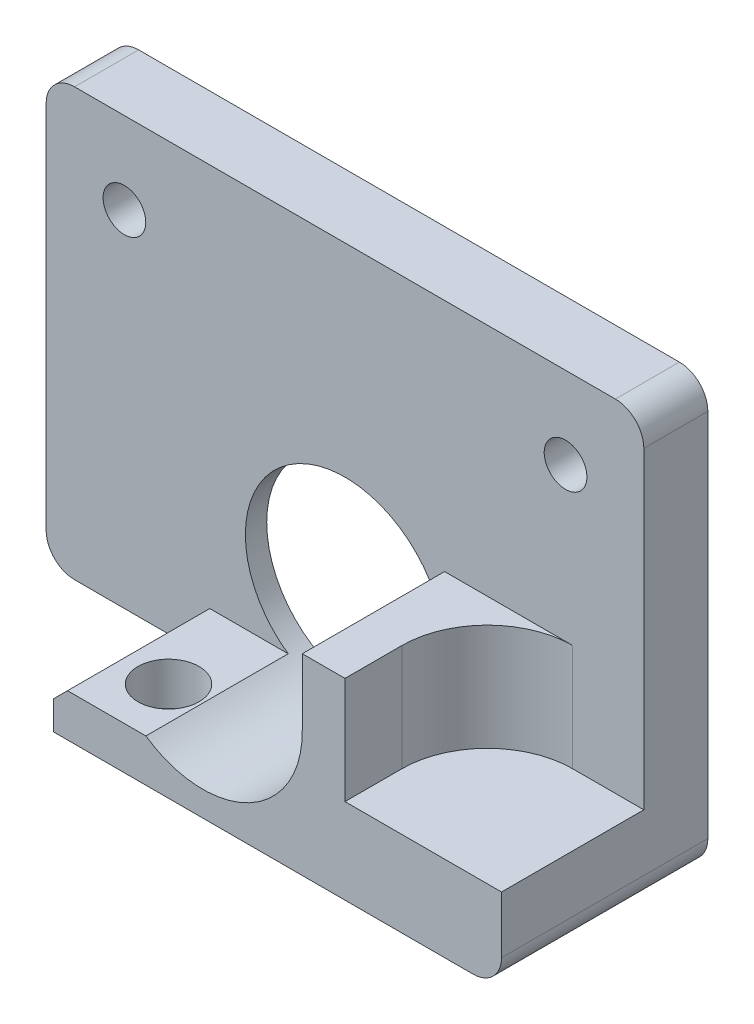
SolidWorks part; units mm, degrees
ref_plane "Front Plane" through (0, 0, 0) normal (0, 0, 1) x (1, 0, 0)
ref_plane "Top Plane" through (0, 0, 0) normal (0, 1, 0) x (1, 0, 0)
ref_plane "Right Plane" through (0, 0, 0) normal (1, 0, 0) x (0, 0, -1)
sketch "Sketch1" plane through (0, 0, 0) normal (0, 0, 1) x (1, 0, 0)
  line L1 (-21, -15) -> (21, -15)
  line L2 (-21, -15) -> (-21, 15)
  line L3 (-21, 15) -> (21, 15)
  line L4 (21, -15) -> (21, 15)
  line L5 (-21, -15) -> (21, 15) construction
  line L6 (-21, 15) -> (21, -15) construction
  point P0 (0, 0)
  dimension "D1" = 42
  dimension "D2" = 30
extrude "Boss-Extrude1" add sketch "Sketch1" along normal blind 4.5
sketch "Sketch2" plane through (0, 0, 4.5) normal (0, 0, 1) x (1, 0, 0)
  line L0 (21, -9) -> (10, -9)
  line L1 (21, -15) -> (21, 15) construction
  line L2 (10, -9) -> (10, -1.5)
  line L3 (10, -1.5) -> (7, -1.5)
  line L4 (7, -1.5) -> (7, -12)
  line L5 (7, -12) -> (-10.5, -12)
  line L6 (-10.5, -12) -> (-10.5, -15)
  line L7 (-21, -15) -> (21, -15) construction
  line L8 (-10.5, -15) -> (21, -15)
  line L9 (21, -15) -> (21, -9)
  dimension "D1" = 31.5
  dimension "D2" = 6
  dimension "D3" = 3
  dimension "D4" = 11
  dimension "D5" = 3
  dimension "D6" = 13.5
extrude "Boss-Extrude2" add sketch "Sketch2" along normal blind 10
fillet "Fillet1" radius 6 2 edges at (7, -12, 9.5) (10, -5.25, 4.5)
sketch "Sketch3" plane through (0, 0, 0) normal (0, 0, -1) x (-1, 0, 0)
  line L0 (-21, 15) -> (21, 15) construction
  line L1 (0, -6.25) -> (0, 15) construction
  circle A0 centre (0, -6.25) radius 11.25
  point P2 (0, 5)
  dimension "D1" = 22.5
  dimension "D2" = 10
extrude "Cut-Extrude1" cut sketch "Sketch3" against normal blind 3
sketch "Sketch4" plane through (0, 0, 3) normal (0, 0, -1) x (-1, 0, 0)
  circle A0 centre (0, -6.25) radius 7
  dimension "D1" = 14
extrude "Cut-Extrude2" cut sketch "Sketch4" against normal through all both and the other way through all
fillet "Fillet2" radius 2 4 edges at (21, -15, 7.25) (21, 15, 2.25) (-21, -15, 2.25) (-21, 15, 2.25)
chamfer "Chamfer1" distance 1 angle 45 1 edges at (-10.5, -12, 9.5)
sketch "Sketch6" plane through (0, -15, 0) normal (0, -1, 0) x (1, 0, 0)
  line L0 (-10.5, 14.5) -> (19, 14.5) construction
  line L1 (-10.5, 14.5) -> (-10.5, 4.5) construction
  circle A0 centre (-6.35, 10.55) radius 2.15
  point P2 (-6.35, 12.7)
  point P5 (-8.5, 10.55)
  dimension "D1" = 4.3
  dimension "D2" = 1.8
  dimension "D3" = 2
extrude "Cut-Extrude4" cut sketch "Sketch6" against normal through all
sketch "Sketch7" plane through (0, 0, 4.5) normal (0, 0, 1) x (1, 0, 0)
  circle A1 centre (-15.5, 9.25) radius 1.5
  circle A2 centre (-15.5, 9.25) radius 1.5
  circle A3 centre (15.5, 9.25) radius 1.5
  circle A4 centre (15.5, 9.25) radius 1.5
  dimension "D1" = 0
  dimension "D2" = 0
extrude "Cut-Extrude5" cut sketch "Sketch7" against normal blind 10
